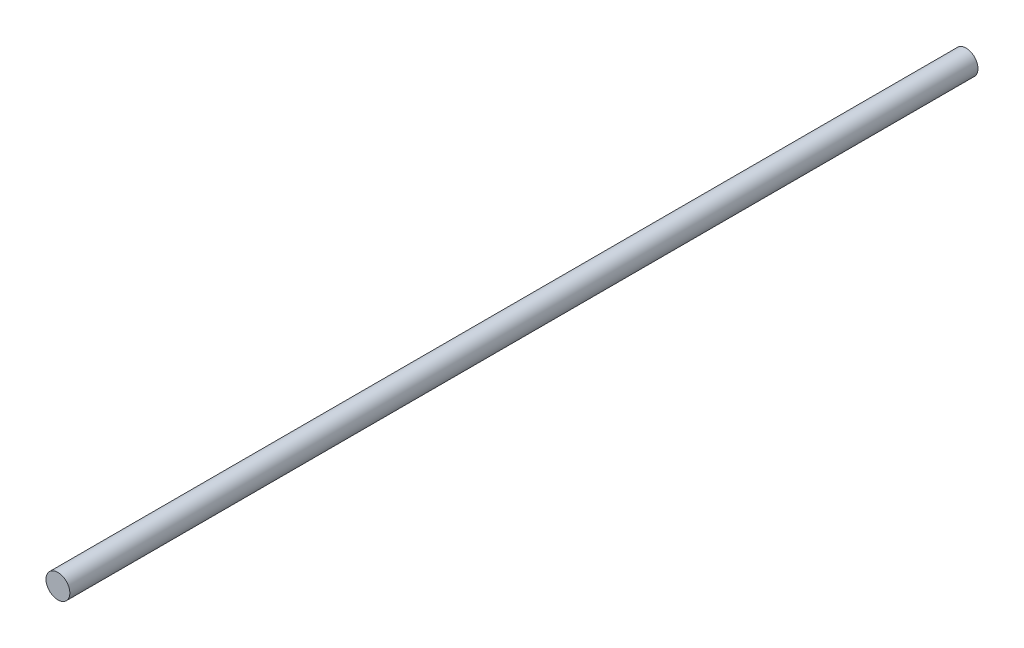
SolidWorks part; units mm, degrees
ref_plane "Front" through (0, 0, 0) normal (0, 0, 1) x (1, 0, 0)
ref_plane "Top" through (0, 0, 0) normal (0, 1, 0) x (1, 0, 0)
ref_plane "Right" through (0, 0, 0) normal (1, 0, 0) x (0, 0, -1)
sketch "Sketch1" plane through (0, 0, 0) normal (0, 0, 1) x (1, 0, 0)
  circle A0 centre (0, 0) radius 3.95
  dimension "D1" = 7.9
extrude "Boss-Extrude1" add sketch "Sketch1" along normal blind 300.7
equation "\"rod_length_zaxis\"=300.7"
equation "\"D1@Boss-Extrude1\"=\"rod_length_zaxis\""
